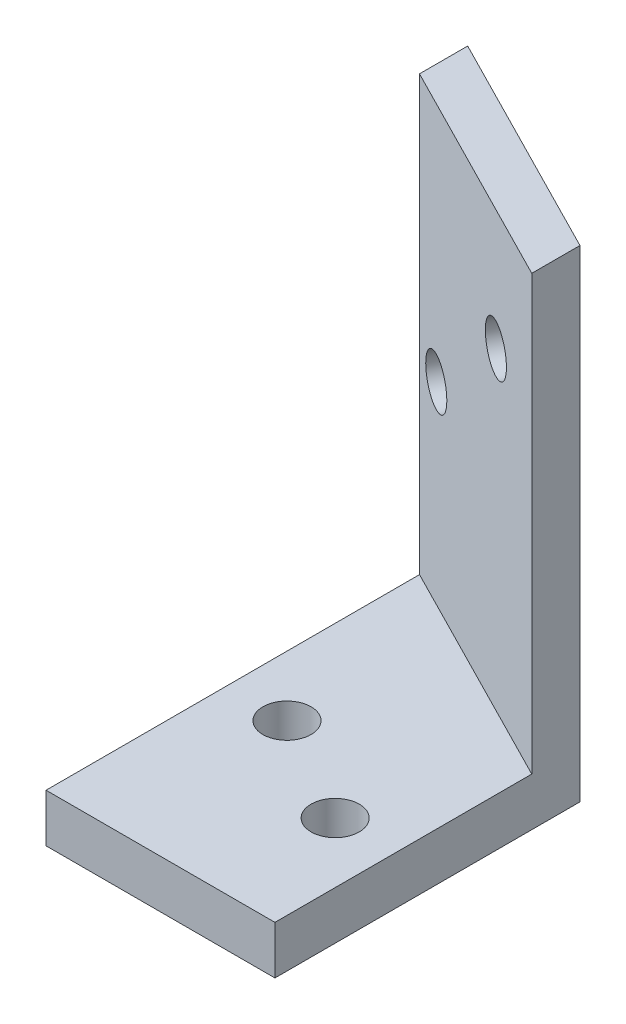
SolidWorks part; units mm, degrees
ref_plane "Front Plane" through (0, 0, 0) normal (0, 0, 1) x (1, 0, 0)
ref_plane "Top Plane" through (0, 0, 0) normal (0, 1, 0) x (1, 0, 0)
ref_plane "Right Plane" through (0, 0, 0) normal (1, 0, 0) x (0, 0, -1)
sketch "Sketch1" plane through (0, 0, 0) normal (0, 1, 0) x (1, 0, 0)
  line L1 (-9.5, -17.5) -> (9.5, -17.5)
  line L2 (-9.5, -17.5) -> (-9.5, 17.5)
  line L3 (-9.5, 17.5) -> (9.5, 17.5)
  line L4 (9.5, -17.5) -> (9.5, 17.5)
  line L5 (-9.5, -17.5) -> (9.5, 17.5) construction
  line L6 (-9.5, 17.5) -> (9.5, -17.5) construction
  point P0 (0, 0)
  dimension "D1" = 19
  dimension "D2" = 35
extrude "Boss-Extrude1" add sketch "Sketch1" along normal blind 4
sketch "Sketch2" plane through (0, 4, 0) normal (0, 1, 0) x (1, 0, 0)
  line L0 (-9.5, 17.5) -> (9.5, 7.819)
  line L1 (9.5, -17.5) -> (9.5, 17.5) construction
  line L2 (-9.5, 17.5) -> (9.5, 17.5)
  line L3 (9.5, 17.5) -> (9.5, 7.819)
  dimension "D1" = 63
extrude "Cut-Extrude1" cut sketch "Sketch2" against normal blind 4
sketch "Sketch3" plane through (0, 4, 0) normal (0, 1, 0) x (1, 0, 0)
  line L0 (-9.5, 17.5) -> (9.5, 7.819)
  line L1 (9.5, 7.819) -> (9.5, 3.819)
  line L2 (9.5, -17.5) -> (9.5, 7.819) construction
  line L3 (9.5, 3.819) -> (-9.5, 13.5)
  line L4 (-9.5, 17.5) -> (-9.5, -17.5) construction
  line L5 (-9.5, 13.5) -> (-9.5, 17.5)
  dimension "D1" = 4
extrude "Boss-Extrude2" add sketch "Sketch3" along normal blind 36
sketch "Sketch4" plane through (5.1209, 0, -10.0503) normal (0.454, 0, -0.891) x (-0.891, 0, -0.454)
  line L0 (-4.9148, 0) -> (-4.9148, 40) construction
  line L1 (16.4094, 40) -> (16.4094, 0) construction
  line L2 (-4.9148, 40) -> (16.4094, 40) construction
  circle A0 centre (0.0852, 30) radius 2
  circle A1 centre (11.4094, 20) radius 2
  dimension "D1" = 4
  dimension "D2" = 4
  dimension "D3" = 5
  dimension "D4" = 5
  dimension "D5" = 10
  dimension "D6" = 10
extrude "Cut-Extrude2" cut sketch "Sketch4" against normal through all
sketch "Sketch5" plane through (0, 4, 0) normal (0, 1, 0) x (1, 0, 0)
  line L0 (9.5, -17.5) -> (9.5, 3.819) construction
  line L1 (-9.5, 13.5) -> (-9.5, -17.5) construction
  line L2 (-9.5, -17.5) -> (9.5, -17.5) construction
  circle A0 centre (-4.5, -2.5) radius 2
  circle A1 centre (4.5, -7.5) radius 2
  dimension "D1" = 4
  dimension "D2" = 4
  dimension "D3" = 5
  dimension "D4" = 5
  dimension "D5" = 15
  dimension "D6" = 10
extrude "Cut-Extrude3" cut sketch "Sketch5" against normal through all
